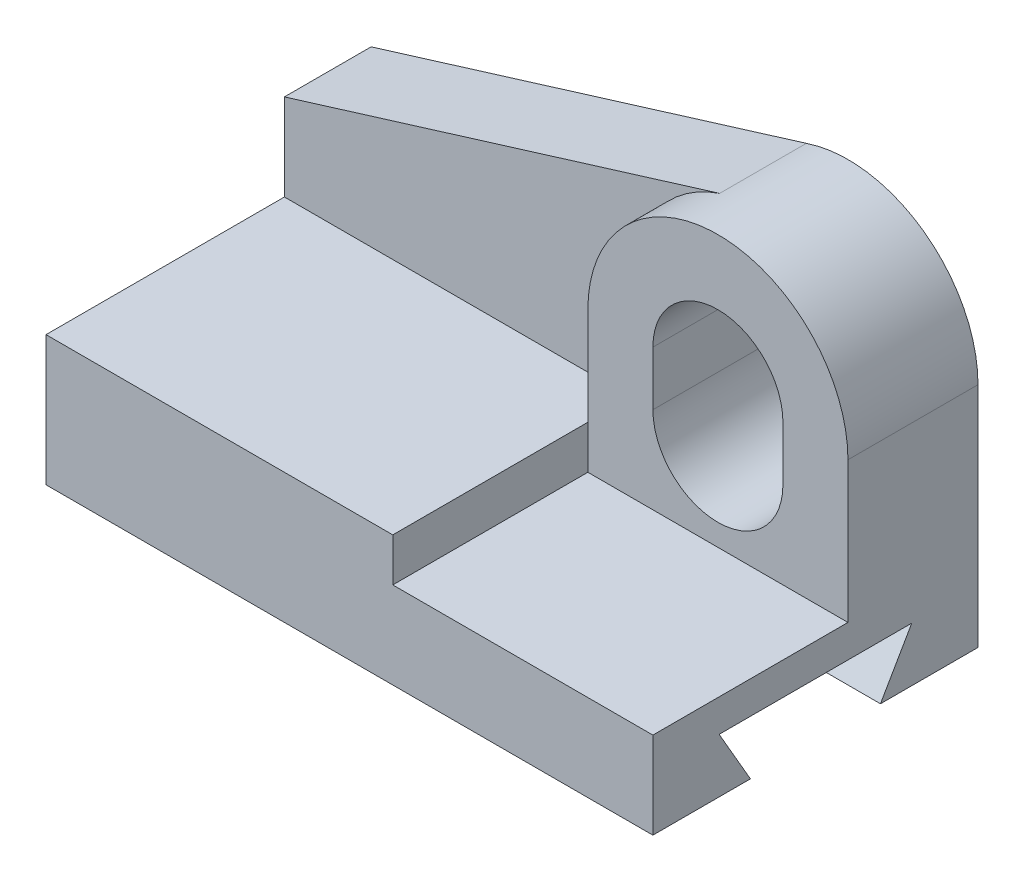
SolidWorks part; units mm, degrees
ref_plane "Front Plane" through (0, 0, 0) normal (0, 0, 1) x (1, 0, 0)
ref_plane "Top Plane" through (0, 0, 0) normal (0, 1, 0) x (1, 0, 0)
ref_plane "Right Plane" through (0, 0, 0) normal (1, 0, 0) x (0, 0, -1)
sketch "Sketch2" plane through (0, 0, 0) normal (0, 0, 1) x (1, 0, 0)
  line L0 (0, 0) -> (56, 0)
  line L1 (56, 0) -> (56, 8)
  line L2 (56, 8) -> (32, 8)
  line L3 (32, 8) -> (32, 12)
  line L4 (32, 12) -> (0, 12)
  line L5 (0, 12) -> (0, 0)
  dimension "D1" = 56
  dimension "D2" = 8
  dimension "D3" = 4
  dimension "D4" = 24
extrude "Boss-Extrude1" add sketch "Sketch2" along normal blind 30
sketch "Sketch3" plane through (0, 0, 0) normal (0, 0, 1) x (1, 0, 0)
  line L0 (32, 8) -> (32, 21)
  line L1 (56, 8) -> (56, 21)
  line L2 (44, 8) -> (44, 18.5) construction
  line L3 (44, 21) -> (44, 16) construction
  line L4 (56, 8) -> (32, 8) construction
  line L5 (50, 21) -> (50, 16)
  line L6 (38, 21) -> (38, 16)
  line L7 (32, 8) -> (56, 8)
  arc A0 (56, 21) -> (32, 21) centre (44, 21) ccw
  arc A1 (50, 21) -> (38, 21) centre (44, 21) ccw
  arc A2 (38, 16) -> (50, 16) centre (44, 16) ccw
  point P13 (44, 18.5)
  dimension "D5" = 6
  dimension "D1" = 13
  dimension "D2" = 13
  dimension "D3" = 10.5
  dimension "D4" = 5
extrude "Boss-Extrude2" add sketch "Sketch3" along normal blind 12
sketch "Sketch4" plane through (0, 0, 0) normal (0, 0, 1) x (1, 0, 0)
  line L0 (0, 12) -> (0, 20)
  line L1 (0, 20) -> (40.7754, 32.5586)
  line L2 (0, 12) -> (32, 12)
  line L3 (32, 21) -> (32, 12)
  arc A0 (56, 21) -> (32, 21) centre (44, 21) ccw construction
  arc A1 (40.7754, 32.5586) -> (32, 21) centre (44, 21) ccw
  dimension "D1" = 8
extrude "Boss-Extrude3" add sketch "Sketch4" along normal blind 8 contours A1 L1 L0 L2 L3
sketch "Sketch5" plane through (0, 0, 0) normal (-1, 0, 0) x (0, 0, 1)
  line L0 (0, 0) -> (30, 0) construction
  line L1 (9, 0) -> (21, 0)
  line L2 (15, 0) -> (15, 9.417) construction
  line L3 (21, 0) -> (23.8868, 5)
  line L4 (23.8868, 5) -> (6.1132, 5)
  line L5 (9, 0) -> (6.1132, 5)
  point P11 (15, 5)
  dimension "D1" = 6
  dimension "D2" = 60
  dimension "D3" = 5
extrude "Cut-Extrude1" cut sketch "Sketch5" against normal through all both
